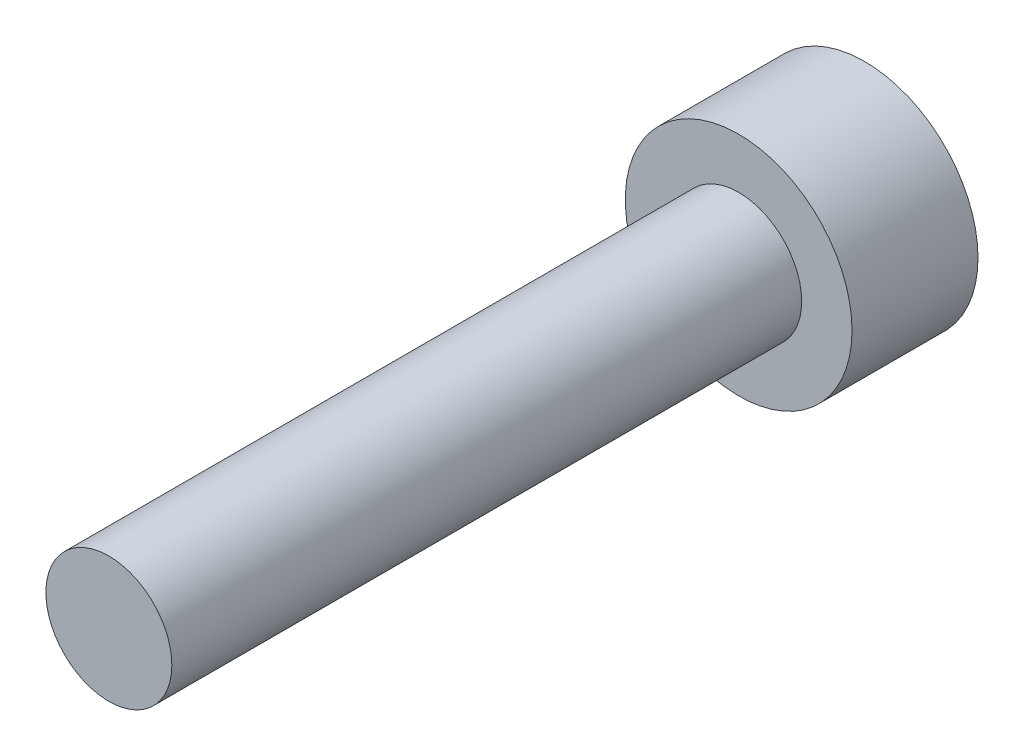
SolidWorks part; units mm, degrees
material "AISI 304"
ref_plane "前视基准面" through (0, 0, 0) normal (0, 0, 1) x (1, 0, 0)
ref_plane "上视基准面" through (0, 0, 0) normal (0, 1, 0) x (1, 0, 0)
ref_plane "右视基准面" through (0, 0, 0) normal (1, 0, 0) x (0, 0, -1)
sketch "草图1" plane through (0, 0, 0) normal (0, 0, 1) x (1, 0, 0)
  circle A0 centre (0, 0) radius 3.6
  dimension "D1" = 7.2
extrude "凸台-拉伸1" add sketch "草图1" along normal blind 4
sketch "草图2" plane through (0, 0, 4) normal (0, 0, 1) x (1, 0, 0)
  circle A0 centre (0, 0) radius 2
  dimension "D1" = 4
extrude "凸台-拉伸2" add sketch "草图2" along normal blind 20
cosmetic thread "装饰螺纹线1" parameters "D2"=3.242
sketch "草图3" plane through (0, 0, 0) normal (0, 0, -1) x (-1, 0, 0)
  line L1 (1.2473, 1.2675) -> (-0.474, 1.7139)
  line L2 (-0.474, 1.7139) -> (-1.7213, 0.4464)
  line L3 (-1.7213, 0.4464) -> (-1.2473, -1.2675)
  line L4 (-1.2473, -1.2675) -> (0.474, -1.7139)
  line L5 (0.474, -1.7139) -> (1.7213, -0.4464)
  line L6 (1.7213, -0.4464) -> (1.2473, 1.2675)
  circle A0 centre (0, 0) radius 1.54 construction
  dimension "D1" = 3.08
extrude "切除-拉伸1" cut sketch "草图3" against normal blind 2
